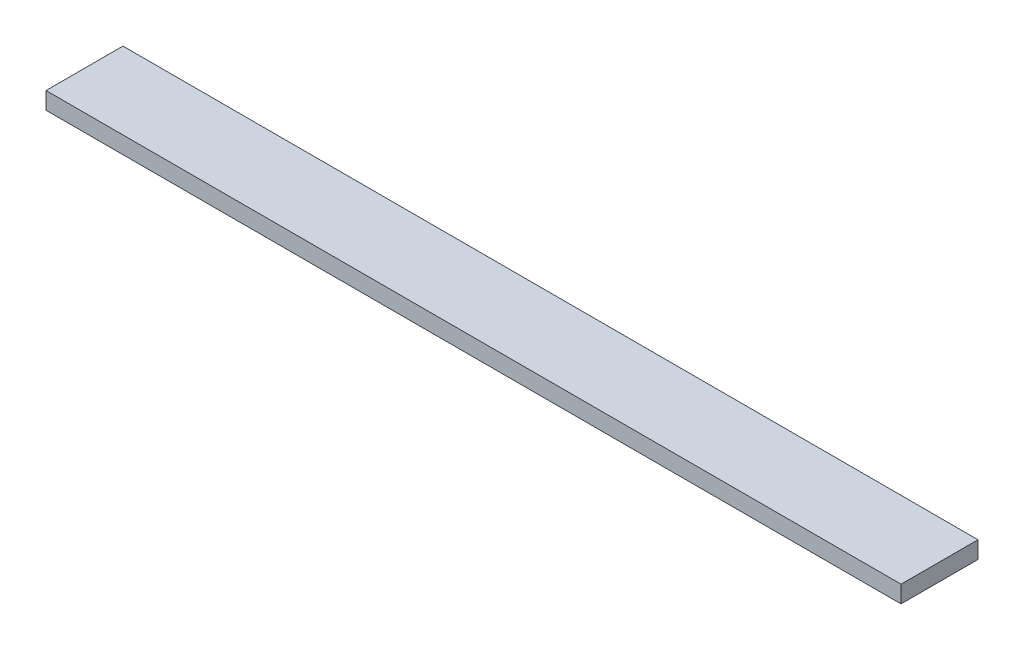
SolidWorks part; units mm, degrees
ref_plane "Front Plane" through (0, 0, 0) normal (0, 0, 1) x (1, 0, 0)
ref_plane "Top Plane" through (0, 0, 0) normal (0, 1, 0) x (1, 0, 0)
ref_plane "Right Plane" through (0, 0, 0) normal (1, 0, 0) x (0, 0, -1)
sketch "Sketch1" plane through (0, 0, 0) normal (1, 0, 0) x (0, 0, -1)
  line L1 (0, 0) -> (45, 0)
  line L2 (0, 0) -> (0, 10)
  line L3 (0, 10) -> (45, 10)
  line L4 (45, 0) -> (45, 10)
  dimension "D1" = 45
  dimension "D2" = 10
extrude "Boss-Extrude1" add sketch "Sketch1" along normal blind 500
ref_plane "Plane1" through (0, 0, -22.5) normal (0, 0, 1) x (1, 0, 0)
ref_plane "Plane2" through (250, 0, 0) normal (-1, 0, 0) x (0, 0, 1)
